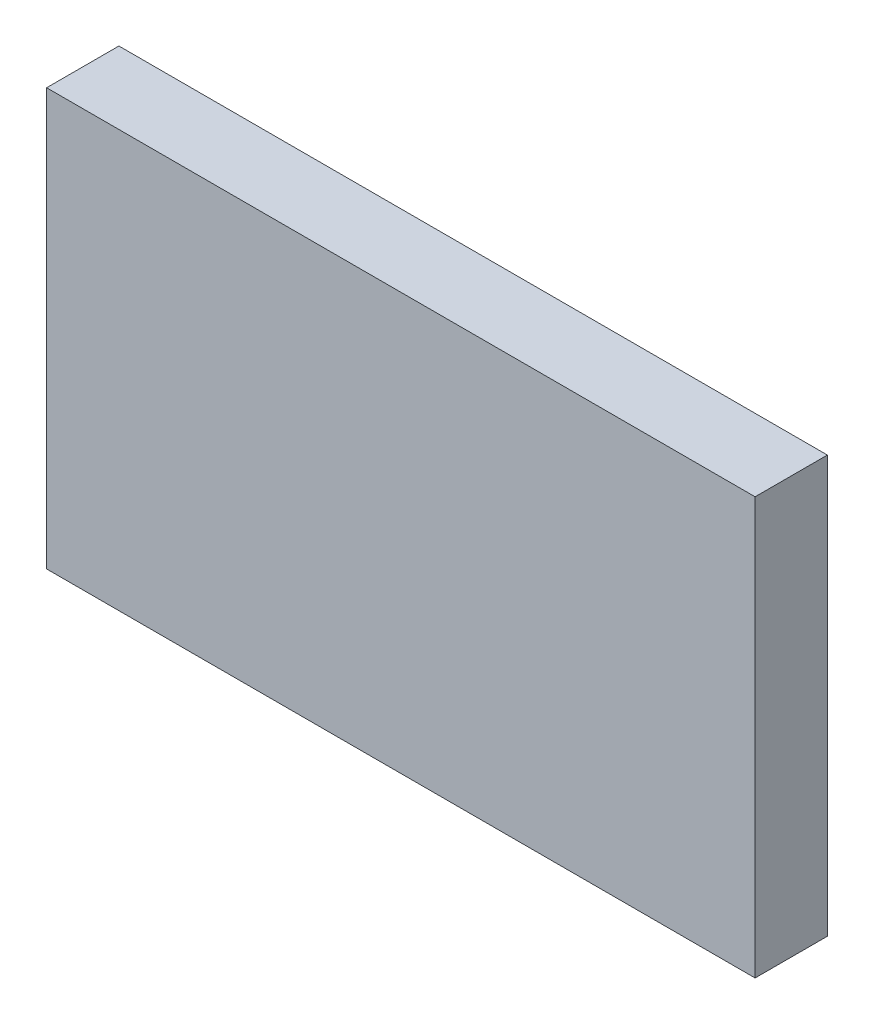
SolidWorks part; units mm, degrees
ref_plane "PLAN_DESSUS" through (0, 0, 0) normal (0, 0, 1) x (1, 0, 0)
ref_plane "PLAN_FACE" through (0, 0, 0) normal (0, 1, 0) x (1, 0, 0)
ref_plane "PLAN_DROITE" through (0, 0, 0) normal (1, 0, 0) x (0, 0, -1)
sketch "Esquisse1" plane through (0, 0, 0) normal (0, 0, 1) x (1, 0, 0)
  line L1 (-105.1298, 60.3648) -> (-7.1217, 60.3648)
  line L2 (-105.1298, 60.3648) -> (-105.1298, 2.713)
  line L3 (-105.1298, 2.713) -> (-7.1217, 2.713)
  line L4 (-7.1217, 60.3648) -> (-7.1217, 2.713)
  line L5 (-105.1298, 60.3648) -> (-7.1217, 2.713) construction
  line L6 (-105.1298, 2.713) -> (-7.1217, 60.3648) construction
  point P0 (-56.1257, 31.5389)
extrude "Boss.-Extru.1" add sketch "Esquisse1" along normal blind 10
